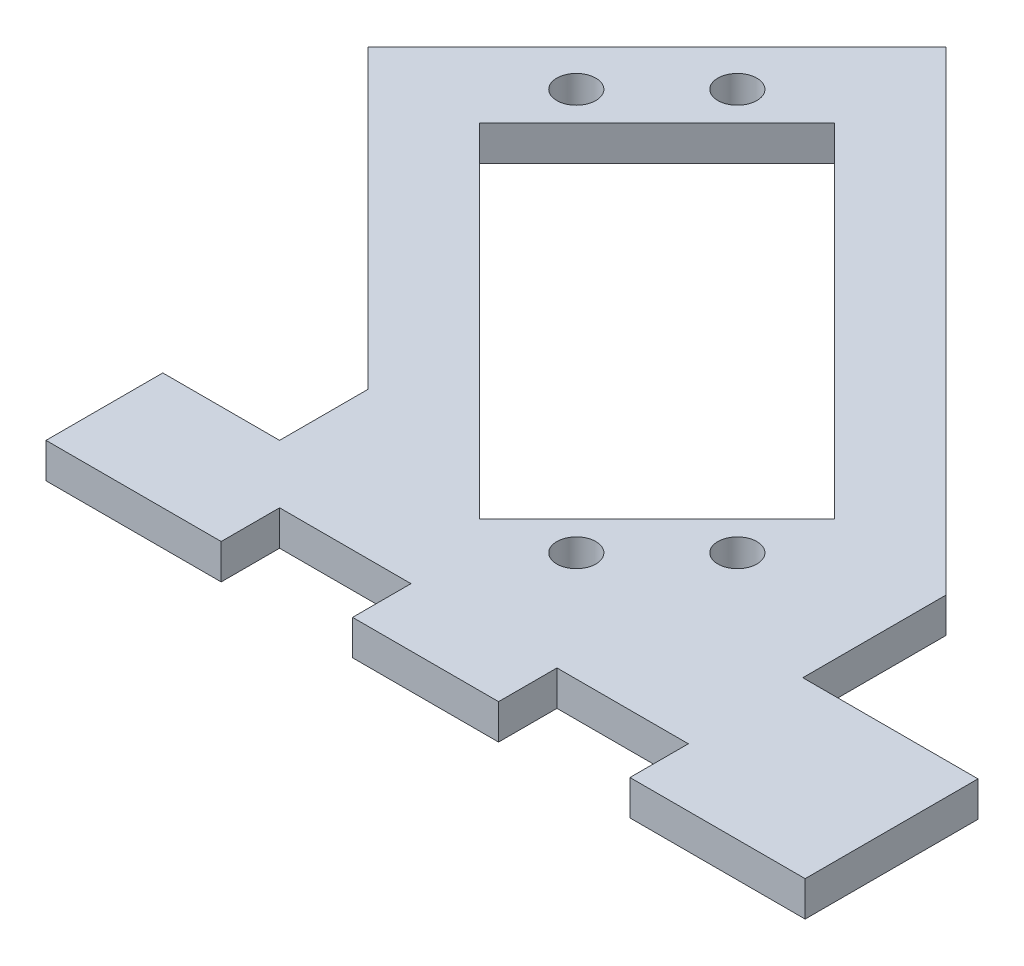
SolidWorks part; units mm, degrees
ref_plane "前视基准面" through (0, 0, 0) normal (0, 0, 1) x (1, 0, 0)
ref_plane "上视基准面" through (0, 0, 0) normal (0, 1, 0) x (1, 0, 0)
ref_plane "右视基准面" through (0, 0, 0) normal (1, 0, 0) x (0, 0, -1)
sketch "草图1" plane through (0, 0, 0) normal (0, 1, 0) x (1, 0, 0)
  line L0 (0, 0) -> (-31244.4874, 0) construction
  line L1 (0, 0) -> (0, -31244.4874) construction
  line L2 (0, 0) -> (15.2028, 15.2028)
  line L3 (15.2028, 15.2028) -> (-14.1421, 44.5477)
  line L4 (-14.1421, 44.5477) -> (-29.3449, 29.3449)
  line L5 (-29.3449, 29.3449) -> (0, 0)
  line L8 (-14.376, 4.8301) -> (-14.376, -2.7224)
  line L9 (-14.376, -2.7224) -> (-24.376, -2.7224)
  line L10 (-24.376, -2.7224) -> (-24.376, -12.7224)
  line L11 (-24.376, -12.7224) -> (-9.376, -12.7224)
  line L12 (-9.376, -12.7224) -> (-9.376, -7.7224)
  line L13 (-9.376, -7.7224) -> (1.874, -7.7224)
  line L14 (1.874, -7.7224) -> (1.874, -12.7224)
  line L15 (1.874, -12.7224) -> (14.374, -12.7224)
  line L16 (14.374, -12.7224) -> (14.374, -7.7224)
  line L17 (14.374, -7.7224) -> (25.624, -7.7224)
  line L18 (25.624, -7.7224) -> (25.624, -12.7224)
  line L19 (25.624, -12.7224) -> (40.624, -12.7224)
  line L20 (40.624, -12.7224) -> (40.624, 2.0776)
  line L23 (25.624, 2.0776) -> (40.624, 2.0776)
  line L24 (-14.376, 4.8301) -> (-39.7748, 30.2288)
  line L25 (-39.7748, 30.2288) -> (-15.026, 54.9776)
  line L26 (-15.026, 54.9776) -> (25.624, 14.3276)
  line L28 (25.624, 14.3276) -> (25.624, 2.0776)
  line L29 (0.5303, 29.8753) -> (-35354.8087, -35325.4638) construction
  line L30 (-21.7435, 36.9463) -> (35333.5955, -35318.3927) construction
  circle A1 centre (-20.8066, 42.9037) radius 1.6702
  circle A5 centre (-27.7009, 36.0094) radius 1.6702
  circle A6 centre (6.6645, 1.644) radius 1.6702
  circle A7 centre (13.5588, 8.5383) radius 1.6702
  point P31 (7.6014, 7.6014)
  point P38 (-21.7435, 36.9463)
  point P40 (-14.6725, 14.6725)
  point P41 (0.5303, 29.8753)
  point P43 (0, 0)
  point P44 (0, 0)
  point P45 (-25.2655, 40.4683)
  dimension "D13" = 6.75
  dimension "D2" = 65
  dimension "D3" = 5
  dimension "D4" = 5
  dimension "D5" = 10
  dimension "D6" = 10
  dimension "D7" = 12.5
  dimension "D8" = 11.25
  dimension "D9" = 15
  dimension "D10" = 14.8
  dimension "D11" = 12.25
  dimension "D12" = 8
  dimension "D14" = 45
  dimension "D15" = 15
  dimension "D16" = 35
  dimension "D17" = 67.7
  dimension "D18" = 48.6
  dimension "D19" = 9.75
extrude "凸台-拉伸1" add sketch "草图1" along normal blind 3
